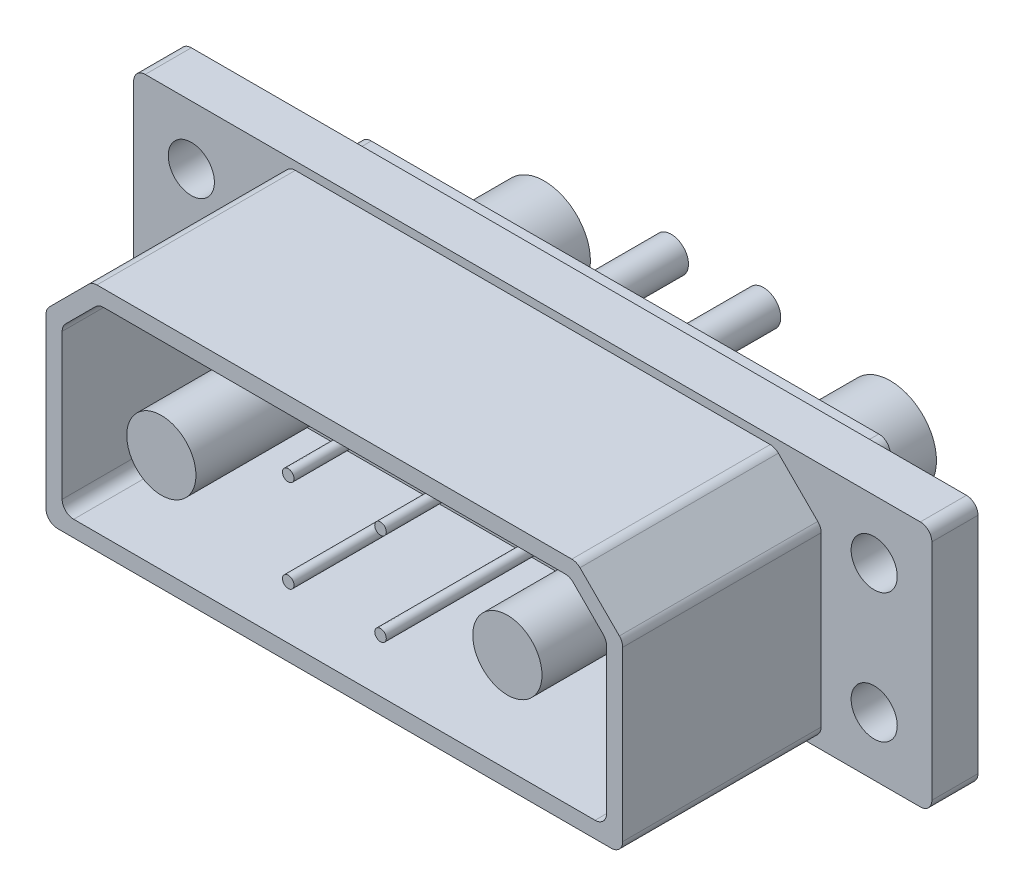
SolidWorks part; units mm, degrees
ref_plane "前视基准面" through (0, 0, 0) normal (0, 0, 1) x (1, 0, 0)
ref_plane "上视基准面" through (0, 0, 0) normal (0, 1, 0) x (1, 0, 0)
ref_plane "右视基准面" through (0, 0, 0) normal (1, 0, 0) x (0, 0, -1)
sketch "草图1" plane through (0, 0, 0) normal (0, 0, 1) x (1, 0, 0)
  line L1 (-17.3, -5.35) -> (17.3, -5.35)
  line L2 (-17.3, -5.35) -> (-17.3, 5.35)
  line L3 (-17.3, 5.35) -> (17.3, 5.35)
  line L4 (17.3, -5.35) -> (17.3, 5.35)
  line L5 (-17.3, -5.35) -> (17.3, 5.35) construction
  line L6 (-17.3, 5.35) -> (17.3, -5.35) construction
  point P0 (0, 0)
  dimension "D1" = 34.6
  dimension "D2" = 10.7
extrude "凸台-拉伸1" add sketch "草图1" along normal blind 2
sketch "草图2" plane through (0, 0, 2) normal (0, 0, 1) x (1, 0, 0)
  line L0 (-2.3087, 0) -> (2.255, 0) construction
  line L1 (0, 2.698) -> (0, -2.7785) construction
  circle A0 centre (-14.8, 2.8) radius 1
  circle A1 centre (14.8, 2.8) radius 1
  circle A2 centre (14.8, -2.8) radius 1
  circle A3 centre (-14.8, -2.8) radius 1
  dimension "D1" = 2
  dimension "D2" = 29.6
  dimension "D3" = 5.6
extrude "切除-拉伸1" cut sketch "草图2" against normal up to surface (2 mm away) up to face at (0, 0, 0)
sketch "草图3" plane through (0, 0, 2) normal (0, 0, 1) x (1, 0, 0)
  line L5 (0, -1.6163) -> (0, 2.1623) construction
  line L6 (10.5, 5) -> (-10.5, 5)
  line L7 (-10.5, 5) -> (-12.5, 3)
  line L9 (-12.5, 3) -> (-12.5, -5)
  line L10 (-12.5, -5) -> (12.5, -5)
  line L11 (-2.5784, 0) -> (1.8816, 0) construction
  line L12 (12.5, 3) -> (12.5, -5)
  line L13 (10.5, 5) -> (12.5, 3)
  point P11 (0, -5)
  point P13 (0, 5)
  dimension "D1" = 10
  dimension "D2" = 25
  dimension "D3" = 2
  dimension "D4" = 2
extrude "凸台-拉伸2" add sketch "草图3" along normal blind 8.6
sketch "草图4" plane through (0, 0, 10.6) normal (0, 0, 1) x (1, 0, 0)
  line L6 (-10.2101, 4.3) -> (-11.8, 2.7101)
  line L7 (-10.2101, 4.3) -> (-11.8, 2.7101)
  line L8 (-11.8, -4.3) -> (11.8, -4.3)
  line L9 (-11.8, -4.3) -> (11.8, -4.3)
  line L10 (11.8, -4.3) -> (11.8, 2.7101)
  line L11 (11.8, -4.3) -> (11.8, 2.7101)
  line L12 (11.8, 2.7101) -> (10.2101, 4.3)
  line L13 (11.8, 2.7101) -> (10.2101, 4.3)
  line L14 (10.2101, 4.3) -> (-10.2101, 4.3)
  line L15 (10.2101, 4.3) -> (-10.2101, 4.3)
  line L17 (-11.8, 2.7101) -> (-11.8, -4.3)
  line L23 (-11.8, 2.7101) -> (-11.8, -4.3)
  dimension "D1" = 0.7
extrude "切除-拉伸2" cut sketch "草图4" against normal blind 8.5
sketch "草图5" plane through (0, 0, 2.1) normal (0, 0, 1) x (1, 0, 0)
  line L0 (-1.745, 0) -> (1.9597, 0) construction
  line L1 (0, -1.8926) -> (0, 2.4295) construction
  circle A0 centre (-7.5, 0) radius 1.5
  circle A1 centre (-2, 2) radius 0.25
  circle A2 centre (2, 2) radius 0.25
  circle A3 centre (7.5, 0) radius 1.5
  circle A4 centre (2, -2) radius 0.25
  circle A5 centre (-2, -2) radius 0.25
  dimension "D1" = 3
  dimension "D3" = 0.5
  dimension "D2" = 15
  dimension "D4" = 4
  dimension "D5" = 4
extrude "凸台-拉伸3" add sketch "草图5" along normal up to surface (8.5 mm away) up to face at (0, 0.9034, 10.6)
sketch "草图6" plane through (0, 0, 0) normal (0, 0, -1) x (-1, 0, 0)
  line L1 (-11.5, -3.75) -> (11.5, -3.75)
  line L2 (-11.5, -3.75) -> (-11.5, 3.75)
  line L3 (-11.5, 3.75) -> (11.5, 3.75)
  line L4 (11.5, -3.75) -> (11.5, 3.75)
  line L5 (-11.5, -3.75) -> (11.5, 3.75) construction
  line L6 (-11.5, 3.75) -> (11.5, -3.75) construction
  point P0 (0, 0)
  dimension "D1" = 23
  dimension "D2" = 7.5
extrude "凸台-拉伸4" add sketch "草图6" along normal blind 2
sketch "草图7" plane through (0, 0, -2) normal (0, 0, -1) x (-1, 0, 0)
  line L0 (-2.3087, 0) -> (2.604, 0) construction
  line L1 (0, -2.3221) -> (0, 3.3423) construction
  circle A0 centre (-7.5, 0) radius 2
  circle A1 centre (-2, 2) radius 0.75
  circle A2 centre (2, 2) radius 0.75
  circle A3 centre (7.5, 0) radius 2
  circle A4 centre (2, -2) radius 0.75
  circle A5 centre (-2, -2) radius 0.75
  dimension "D1" = 4
  dimension "D3" = 1.5
  dimension "D2" = 15
  dimension "D4" = 4
  dimension "D5" = 4
extrude "凸台-拉伸5" add sketch "草图7" along normal blind 4
fillet "圆角2" radius 0.5 20 edges at (-10.5, 5, 6.3) (10.5, 5, 6.3) (12.5, -5, 6.3) (-12.5, -5, 6.3) (-12.5, 3, 6.3) (-10.2101, 4.3, 6.35) (-11.8, 2.7101, 6.35) (-11.8, -4.3, 6.35) (11.8, -4.3, 6.35) (11.8, 2.7101, 6.35) (10.2101, 4.3, 6.35) (12.5, 3, 6.3) (17.3, -5.35, 1) (-17.3, -5.35, 1) (-17.3, 5.35, 1) (17.3, 5.35, 1) (-11.5, -3.75, -1) (11.5, -3.75, -1) (-11.5, 3.75, -1) (11.5, 3.75, -1)
